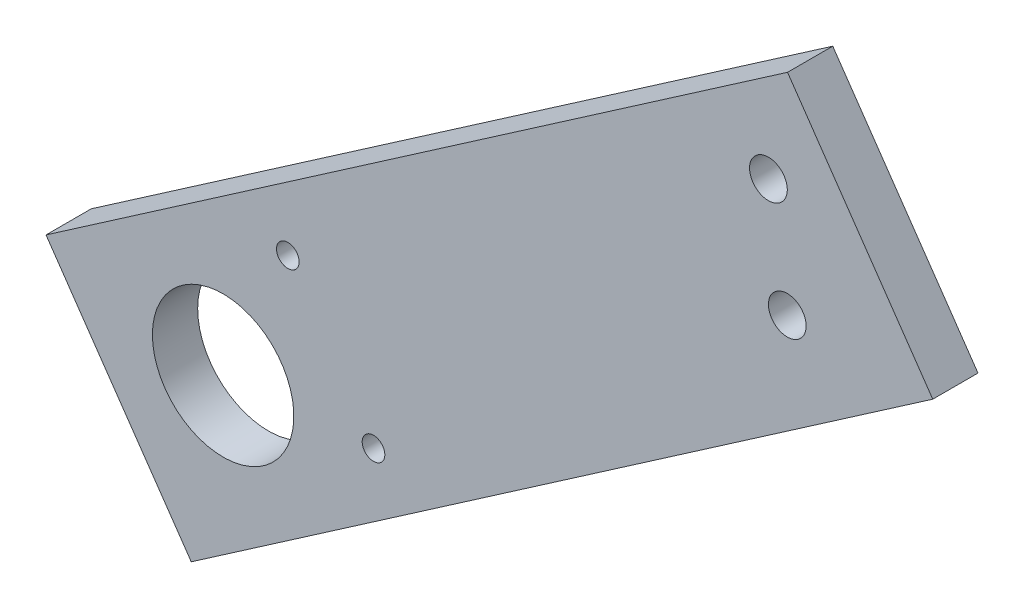
SolidWorks part; units mm, degrees
ref_plane "Front Plane" through (0, 0, 0) normal (0, 0, 1) x (1, 0, 0)
ref_plane "Top Plane" through (0, 0, 0) normal (0, 1, 0) x (1, 0, 0)
ref_plane "Right Plane" through (0, 0, 0) normal (1, 0, 0) x (0, 0, -1)
sketch "Sketch1" plane through (0, 0, 0) normal (0, 0, 1) x (1, 0, 0)
  line L0 (552.9571, 142.8717) -> (562.737, 128.6963)
  line L1 (552.9571, 142.8717) -> (503.0236, 108.4214)
  line L2 (562.737, 128.6963) -> (512.8035, 94.2461)
  line L3 (503.0236, 108.4214) -> (512.8035, 94.2461)
  circle A0 centre (551.6723, 136.0122) radius 1.27
  circle A1 centre (552.9423, 128.6963) radius 1.27
  circle A2 centre (514.951, 106.1891) radius 4.7625
  circle A3 centre (519.3086, 115.3672) radius 0.762
  circle A4 centre (525.0783, 107.0044) radius 0.762
extrude "Boss-Extrude1" add sketch "Sketch1" along normal blind 3.048
